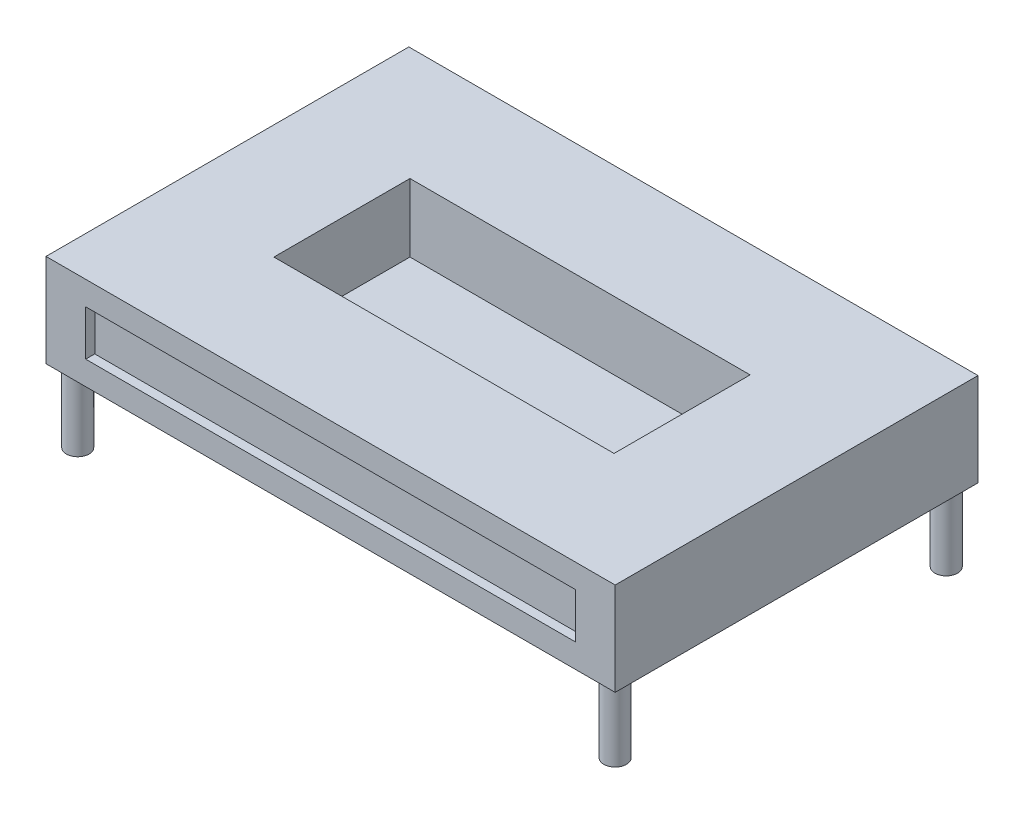
SolidWorks part; units mm, degrees
material "3.0205 (EN-AW 1200)"
ref_plane "前视基准面" through (0, 0, 0) normal (0, 0, 1) x (1, 0, 0)
ref_plane "上视基准面" through (0, 0, 0) normal (0, 1, 0) x (1, 0, 0)
ref_plane "右视基准面" through (0, 0, 0) normal (1, 0, 0) x (0, 0, -1)
other "Configuration Table"
sketch "草图2" plane through (0, 0, 0) normal (0, 1, 0) x (1, 0, 0)
  line L1 (-62.75, -40) -> (62.75, -40)
  line L2 (-62.75, -40) -> (-62.75, 40)
  line L3 (-62.75, 40) -> (62.75, 40)
  line L4 (62.75, -40) -> (62.75, 40)
  line L5 (-62.75, -40) -> (62.75, 40) construction
  line L6 (-62.75, 40) -> (62.75, -40) construction
  point P0 (0, 0)
  dimension "D1" = 80
  dimension "D2" = 125.5
extrude "凸台-拉伸1" add sketch "草图2" along normal mid plane 20.5
sketch "草图3" plane through (0, 10.25, 0) normal (0, 1, 0) x (1, 0, 0)
  line L1 (-37.5, -15) -> (37.5, -15)
  line L2 (-37.5, -15) -> (-37.5, 15)
  line L3 (-37.5, 15) -> (37.5, 15)
  line L4 (37.5, -15) -> (37.5, 15)
  line L5 (-37.5, -15) -> (37.5, 15) construction
  line L6 (-37.5, 15) -> (37.5, -15) construction
  point P0 (0, 0)
  dimension "D1" = 30
  dimension "D2" = 75
extrude "切除-拉伸1" cut sketch "草图3" against normal blind 15
sketch "草图4" plane through (0, -10.25, 0) normal (0, -1, 0) x (1, 0, 0)
  line L0 (62.75, 40) -> (62.75, -40) construction
  line L1 (-62.75, 40) -> (62.75, 40) construction
  circle A0 centre (59.25, 36.5) radius 2.5
  dimension "D1" = 5
  dimension "D2" = 3.5
  dimension "D3" = 3.5
extrude "凸台-拉伸2" add sketch "草图4" along normal blind 16
mirror "镜向1" about plane through (0, 0, 0) normal (1, 0, 0) of "凸台-拉伸2" second plane through (0, 0, 0) second plane normal (0, 0, 1)
sketch "草图5" plane through (0, 0, 40) normal (0, 0, 1) x (1, 0, 0)
  line L1 (-54, -5) -> (54, -5)
  line L2 (-54, -5) -> (-54, 5)
  line L3 (-54, 5) -> (54, 5)
  line L4 (54, -5) -> (54, 5)
  line L5 (-54, -5) -> (54, 5) construction
  line L6 (-54, 5) -> (54, -5) construction
  point P0 (0, 0)
  dimension "D1" = 10
  dimension "D2" = 108
extrude "切除-拉伸2" cut sketch "草图5" against normal blind 2
mirror "镜向2" about plane through (0, 0, 0) normal (0, 0, 1) of "切除-拉伸2"
